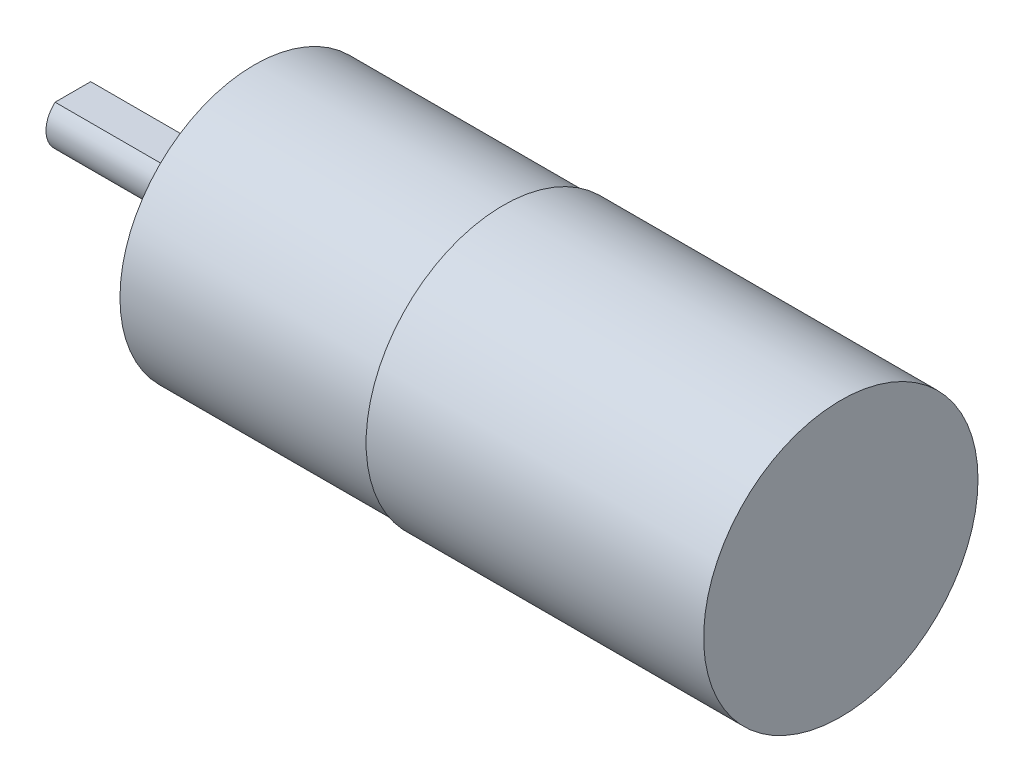
SolidWorks part; units mm, degrees
ref_plane "Front Plane" through (0, 0, 0) normal (0, 0, 1) x (1, 0, 0)
ref_plane "Top Plane" through (0, 0, 0) normal (0, 1, 0) x (1, 0, 0)
ref_plane "Right Plane" through (0, 0, 0) normal (1, 0, 0) x (0, 0, -1)
sketch "Sketch1" plane through (0, 0, 0) normal (1, 0, 0) x (0, 0, -1)
  circle A0 centre (0, 0) radius 10.2
  dimension "D1" = 20.4
extrude "Boss-Extrude1" add sketch "Sketch1" along normal blind 25.1
sketch "Sketch2" plane through (0, 0, 0) normal (-1, 0, 0) x (0, 0, 1)
  circle A0 centre (0, 0) radius 10
  dimension "D1" = 20
extrude "Boss-Extrude2" add sketch "Sketch2" along normal blind 18.5
sketch "Sketch3" plane through (-18.5, 0, 0) normal (-1, 0, 0) x (0, 0, 1)
  circle A0 centre (0, 0) radius 3.5
  dimension "D1" = 7
extrude "Boss-Extrude3" add sketch "Sketch3" along normal blind 3
sketch "Sketch4" plane through (-21.5, 0, 0) normal (-1, 0, 0) x (0, 0, 1)
  circle A0 centre (0, 0) radius 2
  dimension "D1" = 4
extrude "Boss-Extrude4" add sketch "Sketch4" along normal blind 10.5
sketch "Sketch5" plane through (-32, 0, 0) normal (-1, 0, 0) x (0, 0, 1)
  line L0 (-1.3229, 1.5) -> (1.3229, 1.5)
  circle A0 centre (0, 0) radius 2 construction
  circle A1 centre (0, 0) radius 2 construction
  circle A2 centre (0, 0) radius 2
  circle M1 centre (0, 0) radius 2
  dimension "D1" = 1.5
extrude "Cut-Extrude1" cut sketch "Sketch5" along direction (-1, 0, 0) on the side against the normal up to surface (10.5 mm away) contours L0 M1
sketch "Sketch6" plane through (-18.5, 0, 0) normal (-1, 0, 0) x (0, 0, 1)
  circle A0 centre (0, 0) radius 7.5 construction
  circle A1 centre (0, 7.5) radius 1.25
  circle A2 centre (0, -7.5) radius 1.25
  dimension "D1" = 2.5
  dimension "D2" = 2.5
  dimension "D3" = 15
extrude "Cut-Extrude2" cut sketch "Sketch6" against normal blind 3
